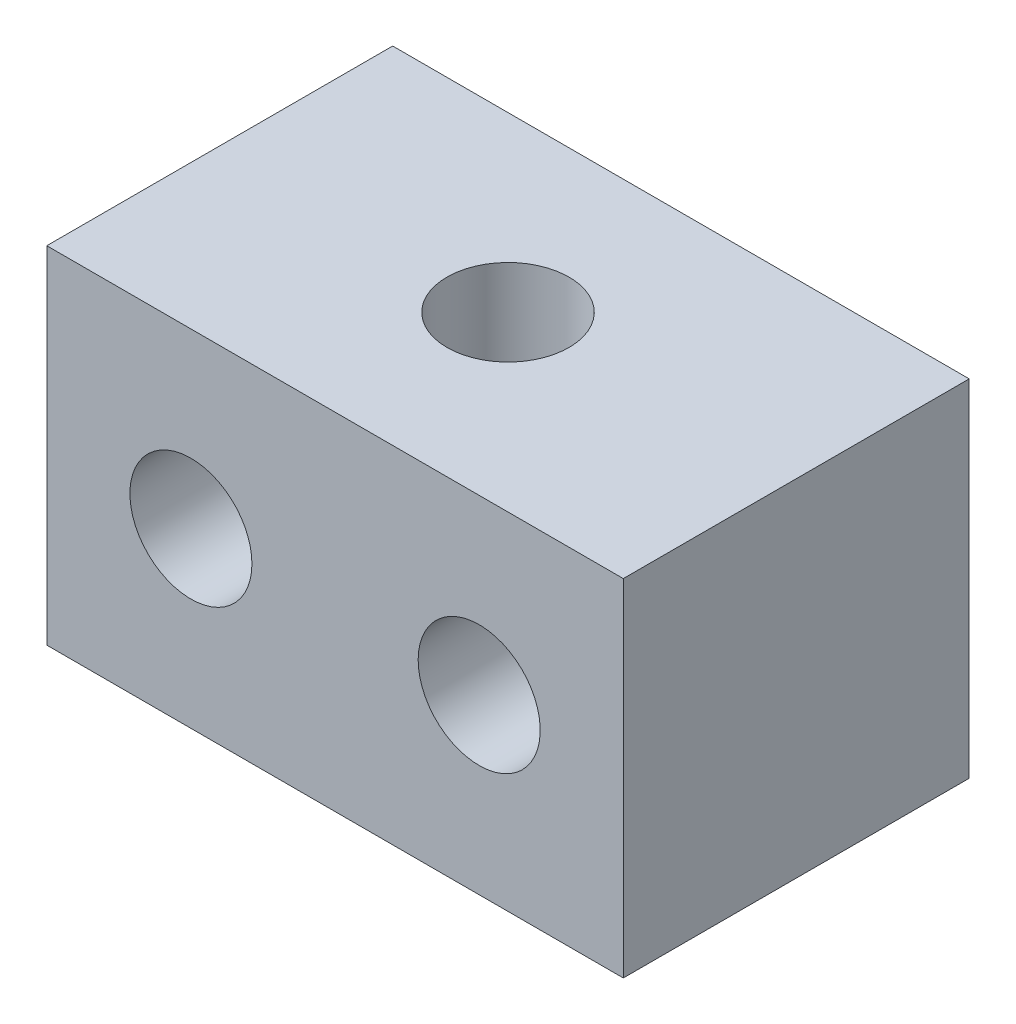
SolidWorks part; units mm, degrees
ref_plane "Front Plane" through (0, 0, 0) normal (0, 0, 1) x (1, 0, 0)
ref_plane "Top Plane" through (0, 0, 0) normal (0, 1, 0) x (1, 0, 0)
ref_plane "Right Plane" through (0, 0, 0) normal (1, 0, 0) x (0, 0, -1)
sketch "Sketch1" plane through (0, 0, 0) normal (0, 1, 0) x (1, 0, 0)
  line L1 (-7.5, 4.5) -> (7.5, 4.5)
  line L2 (-7.5, 4.5) -> (-7.5, -4.5)
  line L3 (-7.5, -4.5) -> (7.5, -4.5)
  line L4 (7.5, 4.5) -> (7.5, -4.5)
  line L5 (-7.5, 4.5) -> (7.5, -4.5) construction
  line L6 (-7.5, -4.5) -> (7.5, 4.5) construction
  point P0 (0, 0)
  dimension "D1" = 9
  dimension "D2" = 15
extrude "Boss-Extrude1" add sketch "Sketch1" along normal blind 9
sketch "Sketch2" plane through (0, 9, 0) normal (0, 1, 0) x (1, 0, 0)
  line L0 (0, 4.5) -> (0, -4.5) construction
  line L1 (7.5, 4.5) -> (-7.5, 4.5) construction
  line L2 (-7.5, -4.5) -> (7.5, -4.5) construction
  line L3 (-7.5, 0) -> (7.5, 0) construction
  line L4 (-7.5, 4.5) -> (-7.5, -4.5) construction
  line L5 (7.5, -4.5) -> (7.5, 4.5) construction
  line L6 (-7.5, 4.5) -> (0, 0) construction
  line L7 (-3.75, 2.25) -> (-3.75, -4.5) construction
  circle A0 centre (-3.75, 0) radius 1.5875
  circle A1 centre (3.75, 0) radius 1.5875
  circle A2 centre (0, 0) radius 1.5875
  dimension "D1" = 3.175
extrude "Cut-Extrude1" cut sketch "Sketch2" against normal through all contours A2
sketch "Sketch3" plane through (0, 0, 4.5) normal (0, 0, 1) x (1, 0, 0)
  line L0 (0, 9) -> (0, 0) construction
  line L1 (-7.5, 9) -> (7.5, 9) construction
  line L2 (-7.5, 4.5) -> (0, 4.5) construction
  line L3 (-7.5, 9) -> (-7.5, 0) construction
  line L4 (-7.5, 9) -> (0, 4.5) construction
  line L5 (-3.75, 6.75) -> (-3.75, 0) construction
  line L6 (-7.5, 0) -> (7.5, 0) construction
  circle A0 centre (-3.75, 4.5) radius 1.5875
  circle A1 centre (3.75, 4.5) radius 1.5875
  dimension "D1" = 3.175
extrude "Cut-Extrude2" cut sketch "Sketch3" against normal through all
